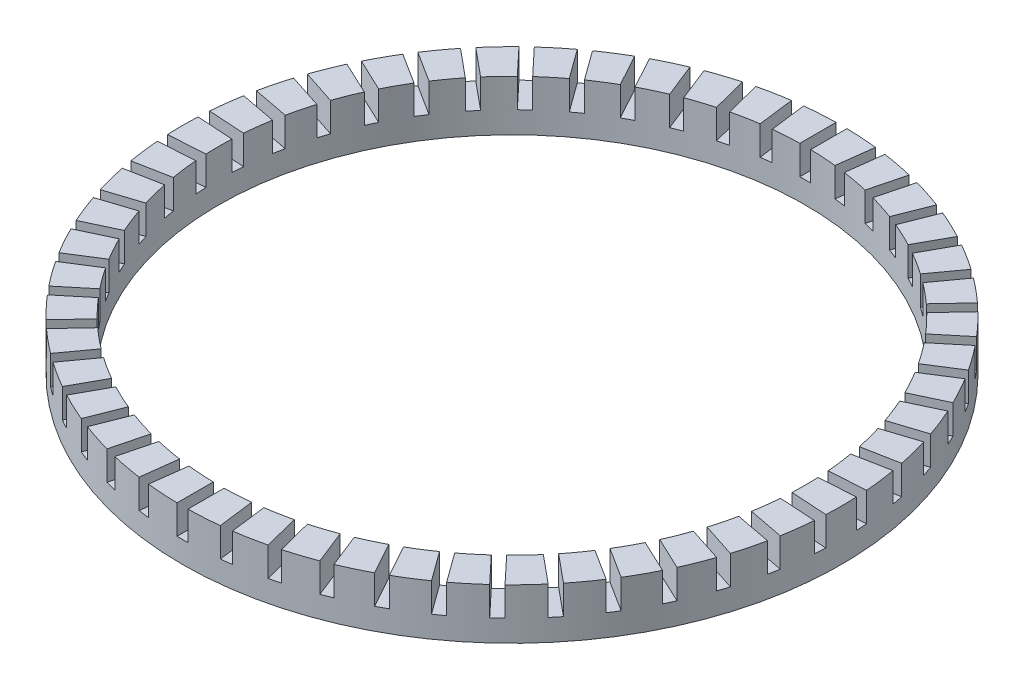
SolidWorks part; units mm, degrees
ref_plane "Front Plane" through (0, 0, 0) normal (0, 0, 1) x (1, 0, 0)
ref_plane "Top Plane" through (0, 0, 0) normal (0, 1, 0) x (1, 0, 0)
ref_plane "Right Plane" through (0, 0, 0) normal (1, 0, 0) x (0, 0, -1)
sketch "Sketch3" plane through (0, 0, 0) normal (0, 0, 1) x (1, 0, 0)
  line L0 (0, 0) -> (0, 38.8642) construction
sketch "Sketch1" plane through (0, 0, 0) normal (0, 1, 0) x (1, 0, 0)
  circle A0 centre (0, 0) radius 40.5
  circle A1 centre (0, 0) radius 45.5
  dimension "D1" = 5
  dimension "D2" = 81
extrude "Boss-Extrude1" add sketch "Sketch1" along normal blind 7
sketch "Sketch2" plane through (0, 7, 0) normal (0, 1, 0) x (1, 0, 0)
  line L0 (0, 0) -> (0, 60.3672) construction
  line L2 (-0.75, 36.4334) -> (0.75, 36.4334)
  line L3 (-0.75, 36.4334) -> (-0.75, 48.4334)
  line L4 (-0.75, 48.4334) -> (0.75, 48.4334)
  line L5 (0.75, 36.4334) -> (0.75, 48.4334)
  line L6 (-0.75, 36.4334) -> (0.75, 48.4334) construction
  line L7 (-0.75, 48.4334) -> (0.75, 36.4334) construction
  circle A0 centre (0, 0) radius 45.1 construction
  circle A1 centre (0, 0) radius 40.1 construction
  point P7 (0, 42.4334)
  dimension "D1" = 1.5
  dimension "D2" = 80.2
extrude "Cut-Extrude1" cut sketch "Sketch2" against normal blind 4
pattern_circular "CirPattern1" count 50 over 360 about axis through (0, 0, 0) along (0, 1, 0) of "Cut-Extrude1"
